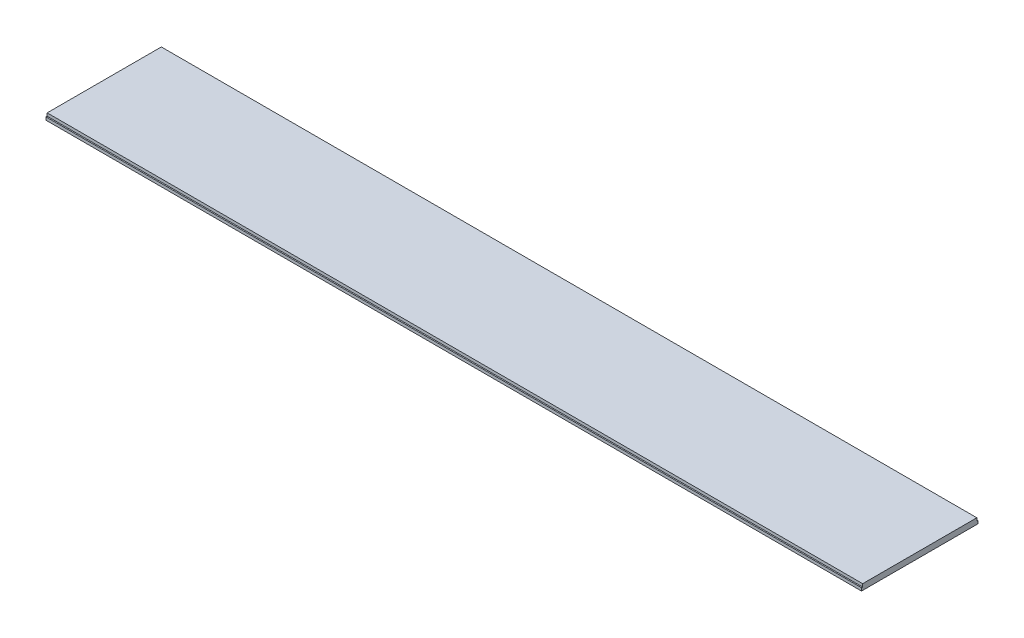
SolidWorks part; units mm, degrees
material "Дуб"
ref_plane "Спереди" through (0, 0, 0) normal (0, 0, 1) x (1, 0, 0)
ref_plane "Сверху" through (0, 0, 0) normal (0, 1, 0) x (1, 0, 0)
ref_plane "Справа" through (0, 0, 0) normal (1, 0, 0) x (0, 0, -1)
sketch "Эскиз1" plane through (0, 0, 0) normal (0, 1, 0) x (1, 0, 0)
  line L1 (-1400, -200) -> (0, -200)
  line L2 (-1400, -200) -> (-1400, 0)
  line L3 (-1400, 0) -> (0, 0)
  line L4 (0, -200) -> (0, 0)
  dimension "D1" = 1400
  dimension "D2" = 200
extrude "Бобышка-Вытянуть1" add sketch "Эскиз1" along normal blind 10
sketch "Эскиз2" plane through (0, 10, 0) normal (0, 1, 0) x (1, 0, 0)
  line L0 (-1400, 0) -> (-1400, -200) construction
  line L1 (0, 0) -> (-1400, 0)
  line L2 (0, 0) -> (0, -2)
  line L3 (0, -2) -> (-1400, -2)
  line L4 (-1400, 0) -> (-1400, -2)
  line L5 (0, -200) -> (0, 0) construction
  line L6 (-1400, -200) -> (0, -200)
  line L7 (-1400, -200) -> (-1400, -198)
  line L8 (-1400, -198) -> (0, -198)
  line L9 (0, -200) -> (0, -198)
  dimension "D1" = 2
extrude "Вырез-Вытянуть1" cut sketch "Эскиз2" against normal blind 5
equation "\"D1@Эскиз1\"=\"L@чистый пол^сборка.SLDASM\""
equation "\"D2@Эскиз1\"=\"B@чистый пол^сборка.SLDASM\""
equation "\"D1@Бобышка-Вытянуть1\"=\"H@чистый пол^сборка.SLDASM\""
equation "\"D1@Вырез-Вытянуть1\"=\"H@чистый пол^сборка.SLDASM\"/2"
